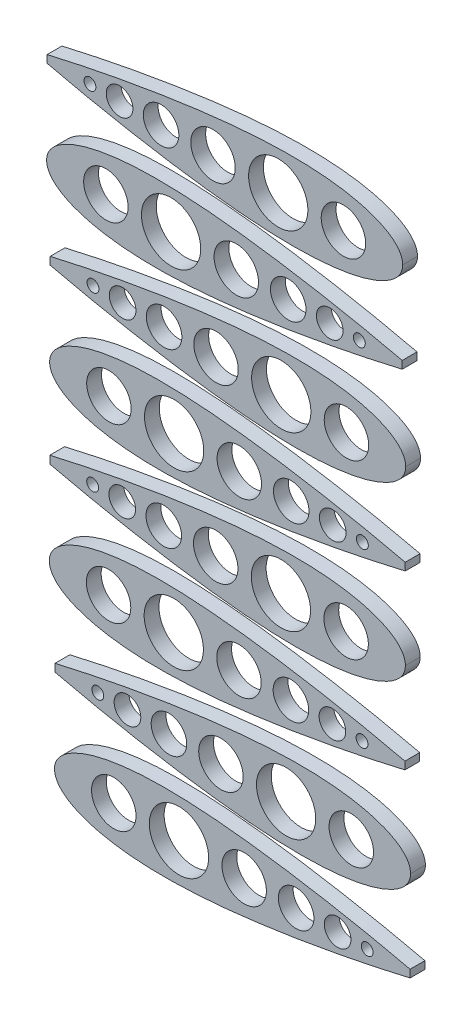
SolidWorks part; units mm, degrees
ref_plane "Front Plane" through (0, 0, 0) normal (0, 0, 1) x (1, 0, 0)
ref_plane "Top Plane" through (0, 0, 0) normal (0, 1, 0) x (1, 0, 0)
ref_plane "Right Plane" through (0, 0, 0) normal (1, 0, 0) x (0, 0, -1)
sketch "Sketch3" plane through (0, 0, 0) normal (0, 0, 1) x (1, 0, 0)
  line L0 (-2.0822, 0.1609) -> (48.226, 0.2196) construction
  line L2 (45.9178, 0.7504) -> (45.9194, -0.2774)
  line L5 (-2.0196, 12.5385) -> (-2.0213, 11.5107)
  line L6 (-2.7831, 24.1357) -> (47.5252, 24.1944) construction
  line L7 (45.2169, 24.7252) -> (45.2185, 23.6974)
  line L9 (-2.7205, 36.5133) -> (-2.7221, 35.4855)
  line L10 (-2.7381, 47.4071) -> (47.5702, 47.4659) construction
  line L11 (45.2619, 47.9966) -> (45.2635, 46.9688)
  line L13 (-2.6755, 59.7848) -> (-2.6771, 58.757)
  line L14 (-3.1458, 70.7938) -> (47.1624, 70.8526) construction
  line L15 (44.8542, 71.3834) -> (44.8558, 70.3556)
  line L17 (-3.0833, 83.1715) -> (-3.0849, 82.1437)
  circle A0 centre (5.9178, 0.1702) radius 3
  circle A1 centre (23.5178, 0.1908) radius 3
  circle A2 centre (30.5311, 0.1989) radius 2.4
  circle A3 centre (36.1311, 0.2055) radius 1.8
  circle A4 centre (14.7178, 0.1805) radius 4
  circle A5 centre (40.1311, 0.2102) radius 0.8
  circle A12 centre (3.7671, 11.9983) radius 0.8
  circle A13 centre (29.1804, 11.9686) radius 4
  circle A14 centre (7.7671, 11.9936) radius 1.8
  circle A15 centre (13.3671, 11.9871) radius 2.4
  circle A16 centre (20.3804, 11.9789) radius 3
  circle A17 centre (37.9804, 11.9584) radius 3
  circle A18 centre (5.2169, 24.145) radius 3
  circle A19 centre (22.8169, 24.1656) radius 3
  circle A20 centre (29.8302, 24.1737) radius 2.4
  circle A21 centre (35.4302, 24.1803) radius 1.8
  circle A22 centre (14.0169, 24.1553) radius 4
  circle A23 centre (39.4302, 24.185) radius 0.8
  circle A24 centre (3.0662, 35.9731) radius 0.8
  circle A25 centre (28.4795, 35.9434) radius 4
  circle A26 centre (7.0662, 35.9684) radius 1.8
  circle A27 centre (12.6662, 35.9619) radius 2.4
  circle A28 centre (19.6795, 35.9537) radius 3
  circle A29 centre (37.2795, 35.9332) radius 3
  circle A30 centre (5.2619, 47.4164) radius 3
  circle A31 centre (22.8619, 47.437) radius 3
  circle A32 centre (29.8752, 47.4452) radius 2.4
  circle A33 centre (35.4752, 47.4517) radius 1.8
  circle A34 centre (14.0619, 47.4267) radius 4
  circle A35 centre (39.4752, 47.4564) radius 0.8
  circle A36 centre (3.1112, 59.2446) radius 0.8
  circle A37 centre (28.5245, 59.2149) radius 4
  circle A38 centre (7.1112, 59.2399) radius 1.8
  circle A39 centre (12.7112, 59.2333) radius 2.4
  circle A40 centre (19.7245, 59.2252) radius 3
  circle A41 centre (37.3245, 59.2046) radius 3
  circle A42 centre (4.8542, 70.8032) radius 3
  circle A43 centre (22.4542, 70.8237) radius 3
  circle A44 centre (29.4675, 70.8319) radius 2.4
  circle A45 centre (35.0675, 70.8385) radius 1.8
  circle A46 centre (13.6542, 70.8135) radius 4
  circle A47 centre (39.0675, 70.8431) radius 0.8
  circle A48 centre (2.7035, 82.6313) radius 0.8
  circle A49 centre (28.1167, 82.6016) radius 4
  circle A50 centre (6.7035, 82.6266) radius 1.8
  circle A51 centre (12.3035, 82.6201) radius 2.4
  circle A52 centre (19.3167, 82.6119) radius 3
  circle A53 centre (36.9167, 82.5913) radius 3
  spline S0 degree 4 poles (-2.0822, 0.1609) (-2.0822, 0.2501) (-2.0745, 0.4065) (-2.0434, 0.6321) (-1.9635, 0.9266) (-1.851, 1.2077) (-1.691, 1.503) (-1.4676, 1.8208) (-1.1589, 2.1675) (-0.73, 2.5509) (-0.1308, 2.9765) (0.6883, 3.4341) (1.8328, 3.9286) (3.2718, 4.3898) (5.3571, 4.8716) (8.0704, 5.2479) (11.2639, 5.4401) (14.9251, 5.4194) (18.1506, 5.2444) (20.9119, 5.0088) (23.6627, 4.7182) (25.9589, 4.4324) (28.2343, 4.1154) (30.9873, 3.6918) (33.2354, 3.3202) (35.5537, 2.9055) (38.2028, 2.4079) (40.5964, 1.9241) (42.6302, 1.4985) (45.3856, 0.8778) (46.7254, 0.5626) (48.6266, 0.1007) (49.5206, -0.1314) (50.2383, -0.3142) (50.4788, -0.3788) (50.6372, -0.4202) (50.7214, -0.4421) knots 0 0 0 0 0 0.006442 0.011325 0.016406 0.022022 0.028285 0.035552 0.044435 0.055515 0.069795 0.088588 0.11215 0.14552 0.17889 0.243189 0.30993 0.376671 0.443412 0.476782 0.510153 0.576893 0.610264 0.643634 0.710375 0.743746 0.777116 0.843857 0.877227 0.910598 0.955299 0.977649 0.988825 0.994412 1 1 1 1 1 construction
  spline S1 degree 4 poles (-2.0822, 0.1609) (-2.0822, 0.2501) (-2.0745, 0.4065) (-2.0434, 0.6321) (-1.9635, 0.9266) (-1.851, 1.2077) (-1.691, 1.503) (-1.4676, 1.8208) (-1.1589, 2.1675) (-0.73, 2.5509) (-0.1308, 2.9765) (0.6883, 3.4341) (1.8328, 3.9286) (3.2718, 4.3898) (5.3571, 4.8716) (8.0704, 5.2479) (11.2639, 5.4401) (14.9251, 5.4194) (18.1506, 5.2444) (20.9119, 5.0088) (23.6627, 4.7182) (25.9589, 4.4324) (28.2343, 4.1154) (30.9873, 3.6918) (33.2354, 3.3202) (35.5537, 2.9055) (38.2028, 2.4079) (40.5964, 1.9241) (42.6302, 1.4985) (44.6943, 1.0335) (45.5086, 0.8461) (45.9178, 0.7504) knots 0 0 0 0 0 0.006442 0.011325 0.016406 0.022022 0.028285 0.035552 0.044435 0.055515 0.069795 0.088588 0.11215 0.14552 0.17889 0.243189 0.30993 0.376671 0.443412 0.476782 0.510153 0.576893 0.610264 0.643634 0.710375 0.743746 0.777116 0.843857 0.877227 0.910598 0.910598 0.910598 0.910598 0.910598
  spline S2 degree 4 poles (-2.0822, 0.1609) (-2.082, 0.0716) (-2.0737, -0.0848) (-2.0419, -0.3102) (-1.961, -0.6045) (-1.8477, -0.8853) (-1.6867, -1.18) (-1.4624, -1.4972) (-1.1526, -1.8429) (-0.7225, -2.2249) (-0.1219, -2.6487) (0.6986, -3.1036) (1.8446, -3.5946) (3.2851, -4.0512) (5.3719, -4.5264) (8.0864, -4.8942) (11.2805, -5.0764) (14.9416, -5.044) (18.1665, -4.8589) (20.9271, -4.6147) (23.6769, -4.3153) (25.9722, -4.0223) (28.2466, -3.6982) (30.9983, -3.2659) (33.2452, -2.8873) (35.5621, -2.4652) (38.2097, -1.9593) (40.6018, -1.468) (42.6342, -1.0359) (44.6969, -0.5644) (45.5105, -0.3744) (45.9194, -0.2774) knots 0 0 0 0 0 0.006442 0.011325 0.016406 0.022022 0.028285 0.035552 0.044435 0.055515 0.069795 0.088588 0.11215 0.14552 0.17889 0.243189 0.30993 0.376671 0.443412 0.476782 0.510153 0.576893 0.610264 0.643634 0.710375 0.743746 0.777116 0.843857 0.877227 0.910598 0.910598 0.910598 0.910598 0.910598
  spline S3 degree 4 poles (-2.7831, 24.1357) (-2.7831, 24.2249) (-2.7754, 24.3813) (-2.7442, 24.6069) (-2.6643, 24.9014) (-2.5519, 25.1825) (-2.3918, 25.4778) (-2.1685, 25.7956) (-1.8598, 26.1423) (-1.4309, 26.5257) (-0.8317, 26.9513) (-0.0125, 27.4089) (1.1319, 27.9034) (2.5709, 28.3646) (4.6562, 28.8464) (7.3695, 29.2228) (10.5631, 29.4149) (14.2242, 29.3942) (17.4498, 29.2192) (20.211, 28.9837) (22.9618, 28.693) (25.258, 28.4072) (27.5334, 28.0902) (30.2864, 27.6666) (32.5346, 27.2951) (34.8528, 26.8803) (37.502, 26.3827) (39.8956, 25.8989) (41.9293, 25.4733) (44.6847, 24.8526) (46.0245, 24.5374) (47.9257, 24.0755) (48.8197, 23.8434) (49.5374, 23.6606) (49.778, 23.596) (49.9364, 23.5546) (50.0205, 23.5327) knots 0 0 0 0 0 0.006442 0.011325 0.016406 0.022022 0.028285 0.035552 0.044435 0.055515 0.069795 0.088588 0.11215 0.14552 0.17889 0.243189 0.30993 0.376671 0.443412 0.476782 0.510153 0.576893 0.610264 0.643634 0.710375 0.743746 0.777116 0.843857 0.877227 0.910598 0.955299 0.977649 0.988825 0.994412 1 1 1 1 1 construction
  spline S4 degree 4 poles (-2.7831, 24.1357) (-2.7831, 24.2249) (-2.7754, 24.3813) (-2.7442, 24.6069) (-2.6643, 24.9014) (-2.5519, 25.1825) (-2.3918, 25.4778) (-2.1685, 25.7956) (-1.8598, 26.1423) (-1.4309, 26.5257) (-0.8317, 26.9513) (-0.0125, 27.4089) (1.1319, 27.9034) (2.5709, 28.3646) (4.6562, 28.8464) (7.3695, 29.2228) (10.5631, 29.4149) (14.2242, 29.3942) (17.4498, 29.2192) (20.211, 28.9837) (22.9618, 28.693) (25.258, 28.4072) (27.5334, 28.0902) (30.2864, 27.6666) (32.5346, 27.2951) (34.8528, 26.8803) (37.502, 26.3827) (39.8956, 25.8989) (41.9293, 25.4733) (43.9935, 25.0083) (44.8077, 24.8209) (45.2169, 24.7252) knots 0 0 0 0 0 0.006442 0.011325 0.016406 0.022022 0.028285 0.035552 0.044435 0.055515 0.069795 0.088588 0.11215 0.14552 0.17889 0.243189 0.30993 0.376671 0.443412 0.476782 0.510153 0.576893 0.610264 0.643634 0.710375 0.743746 0.777116 0.843857 0.877227 0.910598 0.910598 0.910598 0.910598 0.910598
  spline S5 degree 4 poles (45.9804, 11.949) (45.9801, 11.8598) (45.9719, 11.7034) (45.94, 11.4779) (45.8592, 11.1836) (45.7458, 10.9029) (45.5849, 10.6082) (45.3606, 10.291) (45.0507, 9.9453) (44.6206, 9.5632) (44.0201, 9.1395) (43.1995, 8.6846) (42.0535, 8.1936) (40.6131, 7.737) (38.5262, 7.2617) (35.8118, 6.8939) (32.6177, 6.7118) (28.9566, 6.7441) (25.7316, 6.9293) (22.9711, 7.1735) (20.2212, 7.4728) (17.9259, 7.7659) (15.6515, 8.09) (12.8999, 8.5223) (10.653, 8.9009) (8.336, 9.3229) (5.6884, 9.8289) (3.2964, 10.3202) (1.264, 10.7523) (-0.7987, 11.2238) (-1.6123, 11.4137) (-2.0213, 11.5107) knots 0 0 0 0 0 0.006442 0.011325 0.016406 0.022022 0.028285 0.035552 0.044435 0.055515 0.069795 0.088588 0.11215 0.14552 0.17889 0.243189 0.30993 0.376671 0.443412 0.476782 0.510153 0.576893 0.610264 0.643634 0.710375 0.743746 0.777116 0.843857 0.877227 0.910598 0.910598 0.910598 0.910598 0.910598
  spline S6 degree 4 poles (45.9804, 11.949) (45.9804, 12.0382) (45.9727, 12.1947) (45.9415, 12.4202) (45.8616, 12.7148) (45.7491, 12.9959) (45.5891, 13.2911) (45.3658, 13.609) (45.0571, 13.9557) (44.6281, 14.3391) (44.029, 14.7647) (43.2098, 15.2222) (42.0654, 15.7168) (40.6264, 16.178) (38.541, 16.6598) (35.8278, 17.0361) (32.6342, 17.2283) (28.973, 17.2075) (25.7475, 17.0325) (22.9862, 16.797) (20.2355, 16.5063) (17.9392, 16.2205) (15.6639, 15.9036) (12.9108, 15.48) (10.6627, 15.1084) (8.3445, 14.6937) (5.6953, 14.1961) (3.3017, 13.7123) (1.268, 13.2866) (-0.7962, 12.8216) (-1.6104, 12.6342) (-2.0196, 12.5385) knots 0 0 0 0 0 0.006442 0.011325 0.016406 0.022022 0.028285 0.035552 0.044435 0.055515 0.069795 0.088588 0.11215 0.14552 0.17889 0.243189 0.30993 0.376671 0.443412 0.476782 0.510153 0.576893 0.610264 0.643634 0.710375 0.743746 0.777116 0.843857 0.877227 0.910598 0.910598 0.910598 0.910598 0.910598
  spline S7 degree 4 poles (-2.7831, 24.1357) (-2.7828, 24.0464) (-2.7746, 23.89) (-2.7428, 23.6646) (-2.6619, 23.3703) (-2.5486, 23.0895) (-2.3876, 22.7948) (-2.1633, 22.4776) (-1.8535, 22.1319) (-1.4233, 21.7499) (-0.8228, 21.3261) (-0.0022, 20.8712) (1.1438, 20.3802) (2.5842, 19.9236) (4.671, 19.4484) (7.3855, 19.0806) (10.5796, 18.8984) (14.2407, 18.9308) (17.4657, 19.1159) (20.2262, 19.3601) (22.976, 19.6595) (25.2714, 19.9525) (27.5457, 20.2766) (30.2974, 20.7089) (32.5443, 21.0875) (34.8613, 21.5096) (37.5088, 22.0155) (39.9009, 22.5068) (41.9333, 22.9389) (43.996, 23.4104) (44.8096, 23.6004) (45.2185, 23.6974) knots 0 0 0 0 0 0.006442 0.011325 0.016406 0.022022 0.028285 0.035552 0.044435 0.055515 0.069795 0.088588 0.11215 0.14552 0.17889 0.243189 0.30993 0.376671 0.443412 0.476782 0.510153 0.576893 0.610264 0.643634 0.710375 0.743746 0.777116 0.843857 0.877227 0.910598 0.910598 0.910598 0.910598 0.910598
  spline S8 degree 4 poles (45.2795, 35.9238) (45.2792, 35.8346) (45.271, 35.6782) (45.2392, 35.4527) (45.1583, 35.1584) (45.045, 34.8777) (44.884, 34.583) (44.6597, 34.2658) (44.3499, 33.9201) (43.9197, 33.538) (43.3192, 33.1143) (42.4986, 32.6594) (41.3526, 32.1684) (39.9122, 31.7118) (37.8254, 31.2365) (35.1109, 30.8687) (31.9168, 30.6866) (28.2557, 30.7189) (25.0307, 30.9041) (22.2702, 31.1483) (19.5204, 31.4476) (17.225, 31.7407) (14.9507, 32.0648) (12.199, 32.4971) (9.9521, 32.8757) (7.6351, 33.2977) (4.9876, 33.8037) (2.5955, 34.295) (0.5631, 34.7271) (-1.4996, 35.1986) (-2.3132, 35.3885) (-2.7221, 35.4855) knots 0 0 0 0 0 0.006442 0.011325 0.016406 0.022022 0.028285 0.035552 0.044435 0.055515 0.069795 0.088588 0.11215 0.14552 0.17889 0.243189 0.30993 0.376671 0.443412 0.476782 0.510153 0.576893 0.610264 0.643634 0.710375 0.743746 0.777116 0.843857 0.877227 0.910598 0.910598 0.910598 0.910598 0.910598
  spline S9 degree 4 poles (45.2795, 35.9238) (45.2795, 36.013) (45.2718, 36.1695) (45.2407, 36.395) (45.1607, 36.6896) (45.0483, 36.9707) (44.8882, 37.2659) (44.6649, 37.5838) (44.3562, 37.9305) (43.9273, 38.3139) (43.3281, 38.7395) (42.5089, 39.197) (41.3645, 39.6916) (39.9255, 40.1528) (37.8402, 40.6346) (35.1269, 41.0109) (31.9334, 41.2031) (28.2722, 41.1823) (25.0466, 41.0073) (22.2854, 40.7718) (19.5346, 40.4811) (17.2384, 40.1953) (14.963, 39.8784) (12.21, 39.4548) (9.9619, 39.0832) (7.6436, 38.6685) (4.9944, 38.1709) (2.6008, 37.6871) (0.5671, 37.2614) (-1.4971, 36.7964) (-2.3113, 36.609) (-2.7205, 36.5133) knots 0 0 0 0 0 0.006442 0.011325 0.016406 0.022022 0.028285 0.035552 0.044435 0.055515 0.069795 0.088588 0.11215 0.14552 0.17889 0.243189 0.30993 0.376671 0.443412 0.476782 0.510153 0.576893 0.610264 0.643634 0.710375 0.743746 0.777116 0.843857 0.877227 0.910598 0.910598 0.910598 0.910598 0.910598
  spline S10 degree 4 poles (-2.7381, 47.4071) (-2.7381, 47.4963) (-2.7304, 47.6528) (-2.6993, 47.8783) (-2.6193, 48.1729) (-2.5069, 48.454) (-2.3468, 48.7492) (-2.1235, 49.0671) (-1.8148, 49.4138) (-1.3859, 49.7972) (-0.7867, 50.2228) (0.0325, 50.6803) (1.1769, 51.1749) (2.6159, 51.636) (4.7012, 52.1179) (7.4145, 52.4942) (10.6081, 52.6864) (14.2692, 52.6656) (17.4948, 52.4906) (20.256, 52.2551) (23.0068, 51.9644) (25.303, 51.6786) (27.5784, 51.3617) (30.3314, 50.938) (32.5796, 50.5665) (34.8978, 50.1518) (37.547, 49.6542) (39.9406, 49.1704) (41.9743, 48.7447) (44.7297, 48.124) (46.0695, 47.8089) (47.9707, 47.3469) (48.8647, 47.1149) (49.5824, 46.932) (49.823, 46.8674) (49.9813, 46.8261) (50.0655, 46.8042) knots 0 0 0 0 0 0.006442 0.011325 0.016406 0.022022 0.028285 0.035552 0.044435 0.055515 0.069795 0.088588 0.11215 0.14552 0.17889 0.243189 0.30993 0.376671 0.443412 0.476782 0.510153 0.576893 0.610264 0.643634 0.710375 0.743746 0.777116 0.843857 0.877227 0.910598 0.955299 0.977649 0.988825 0.994412 1 1 1 1 1 construction
  spline S11 degree 4 poles (-2.7381, 47.4071) (-2.7381, 47.4963) (-2.7304, 47.6528) (-2.6993, 47.8783) (-2.6193, 48.1729) (-2.5069, 48.454) (-2.3468, 48.7492) (-2.1235, 49.0671) (-1.8148, 49.4138) (-1.3859, 49.7972) (-0.7867, 50.2228) (0.0325, 50.6803) (1.1769, 51.1749) (2.6159, 51.636) (4.7012, 52.1179) (7.4145, 52.4942) (10.6081, 52.6864) (14.2692, 52.6656) (17.4948, 52.4906) (20.256, 52.2551) (23.0068, 51.9644) (25.303, 51.6786) (27.5784, 51.3617) (30.3314, 50.938) (32.5796, 50.5665) (34.8978, 50.1518) (37.547, 49.6542) (39.9406, 49.1704) (41.9743, 48.7447) (44.0385, 48.2797) (44.8527, 48.0923) (45.2619, 47.9966) knots 0 0 0 0 0 0.006442 0.011325 0.016406 0.022022 0.028285 0.035552 0.044435 0.055515 0.069795 0.088588 0.11215 0.14552 0.17889 0.243189 0.30993 0.376671 0.443412 0.476782 0.510153 0.576893 0.610264 0.643634 0.710375 0.743746 0.777116 0.843857 0.877227 0.910598 0.910598 0.910598 0.910598 0.910598
  spline S12 degree 4 poles (-2.7381, 47.4071) (-2.7378, 47.3179) (-2.7296, 47.1615) (-2.6978, 46.936) (-2.6169, 46.6417) (-2.5036, 46.361) (-2.3426, 46.0663) (-2.1183, 45.7491) (-1.8085, 45.4034) (-1.3783, 45.0213) (-0.7778, 44.5976) (0.0428, 44.1427) (1.1888, 43.6517) (2.6292, 43.1951) (4.716, 42.7198) (7.4305, 42.352) (10.6246, 42.1699) (14.2857, 42.2022) (17.5107, 42.3873) (20.2712, 42.6316) (23.021, 42.9309) (25.3164, 43.2239) (27.5907, 43.5481) (30.3424, 43.9803) (32.5893, 44.359) (34.9063, 44.781) (37.5538, 45.287) (39.9459, 45.7783) (41.9783, 46.2104) (44.041, 46.6818) (44.8546, 46.8718) (45.2635, 46.9688) knots 0 0 0 0 0 0.006442 0.011325 0.016406 0.022022 0.028285 0.035552 0.044435 0.055515 0.069795 0.088588 0.11215 0.14552 0.17889 0.243189 0.30993 0.376671 0.443412 0.476782 0.510153 0.576893 0.610264 0.643634 0.710375 0.743746 0.777116 0.843857 0.877227 0.910598 0.910598 0.910598 0.910598 0.910598
  spline S13 degree 4 poles (45.3245, 59.1953) (45.3242, 59.106) (45.316, 58.9496) (45.2842, 58.7242) (45.2033, 58.4299) (45.09, 58.1491) (44.929, 57.8544) (44.7047, 57.5372) (44.3949, 57.1915) (43.9647, 56.8095) (43.3642, 56.3857) (42.5436, 55.9308) (41.3976, 55.4398) (39.9572, 54.9832) (37.8704, 54.508) (35.1559, 54.1402) (31.9618, 53.958) (28.3007, 53.9904) (25.0757, 54.1755) (22.3152, 54.4197) (19.5654, 54.7191) (17.27, 55.0121) (14.9957, 55.3362) (12.244, 55.7685) (9.9971, 56.1471) (7.6801, 56.5692) (5.0326, 57.0751) (2.6405, 57.5664) (0.6081, 57.9985) (-1.4546, 58.47) (-2.2682, 58.66) (-2.6771, 58.757) knots 0 0 0 0 0 0.006442 0.011325 0.016406 0.022022 0.028285 0.035552 0.044435 0.055515 0.069795 0.088588 0.11215 0.14552 0.17889 0.243189 0.30993 0.376671 0.443412 0.476782 0.510153 0.576893 0.610264 0.643634 0.710375 0.743746 0.777116 0.843857 0.877227 0.910598 0.910598 0.910598 0.910598 0.910598
  spline S14 degree 4 poles (45.3245, 59.1953) (45.3245, 59.2845) (45.3168, 59.4409) (45.2857, 59.6665) (45.2057, 59.961) (45.0933, 60.2421) (44.9332, 60.5374) (44.7099, 60.8552) (44.4012, 61.2019) (43.9723, 61.5853) (43.3731, 62.0109) (42.5539, 62.4685) (41.4095, 62.963) (39.9705, 63.4242) (37.8852, 63.906) (35.1719, 64.2823) (31.9783, 64.4745) (28.3172, 64.4538) (25.0916, 64.2788) (22.3304, 64.0433) (19.5796, 63.7526) (17.2834, 63.4668) (15.008, 63.1498) (12.255, 62.7262) (10.0069, 62.3546) (7.6886, 61.9399) (5.0394, 61.4423) (2.6458, 60.9585) (0.6121, 60.5329) (-1.4521, 60.0679) (-2.2663, 59.8805) (-2.6755, 59.7848) knots 0 0 0 0 0 0.006442 0.011325 0.016406 0.022022 0.028285 0.035552 0.044435 0.055515 0.069795 0.088588 0.11215 0.14552 0.17889 0.243189 0.30993 0.376671 0.443412 0.476782 0.510153 0.576893 0.610264 0.643634 0.710375 0.743746 0.777116 0.843857 0.877227 0.910598 0.910598 0.910598 0.910598 0.910598
  spline S15 degree 4 poles (-3.1458, 70.7938) (-3.1458, 70.8831) (-3.1381, 71.0395) (-3.107, 71.2651) (-3.0271, 71.5596) (-2.9146, 71.8407) (-2.7546, 72.1359) (-2.5312, 72.4538) (-2.2225, 72.8005) (-1.7936, 73.1839) (-1.1944, 73.6095) (-0.3753, 74.067) (0.7692, 74.5616) (2.2082, 75.0228) (4.2935, 75.5046) (7.0068, 75.8809) (10.2003, 76.0731) (13.8615, 76.0524) (17.087, 75.8774) (19.8483, 75.6418) (22.5991, 75.3512) (24.8953, 75.0654) (27.1707, 74.7484) (29.9237, 74.3248) (32.1718, 73.9532) (34.4901, 73.5385) (37.1392, 73.0409) (39.5328, 72.5571) (41.5666, 72.1314) (44.322, 71.5107) (45.6618, 71.1956) (47.563, 70.7336) (48.457, 70.5016) (49.1746, 70.3188) (49.4152, 70.2542) (49.5736, 70.2128) (49.6577, 70.1909) knots 0 0 0 0 0 0.006442 0.011325 0.016406 0.022022 0.028285 0.035552 0.044435 0.055515 0.069795 0.088588 0.11215 0.14552 0.17889 0.243189 0.30993 0.376671 0.443412 0.476782 0.510153 0.576893 0.610264 0.643634 0.710375 0.743746 0.777116 0.843857 0.877227 0.910598 0.955299 0.977649 0.988825 0.994412 1 1 1 1 1 construction
  spline S16 degree 4 poles (-3.1458, 70.7938) (-3.1458, 70.8831) (-3.1381, 71.0395) (-3.107, 71.2651) (-3.0271, 71.5596) (-2.9146, 71.8407) (-2.7546, 72.1359) (-2.5312, 72.4538) (-2.2225, 72.8005) (-1.7936, 73.1839) (-1.1944, 73.6095) (-0.3753, 74.067) (0.7692, 74.5616) (2.2082, 75.0228) (4.2935, 75.5046) (7.0068, 75.8809) (10.2003, 76.0731) (13.8615, 76.0524) (17.087, 75.8774) (19.8483, 75.6418) (22.5991, 75.3512) (24.8953, 75.0654) (27.1707, 74.7484) (29.9237, 74.3248) (32.1718, 73.9532) (34.4901, 73.5385) (37.1392, 73.0409) (39.5328, 72.5571) (41.5666, 72.1314) (43.6307, 71.6665) (44.445, 71.4791) (44.8542, 71.3834) knots 0 0 0 0 0 0.006442 0.011325 0.016406 0.022022 0.028285 0.035552 0.044435 0.055515 0.069795 0.088588 0.11215 0.14552 0.17889 0.243189 0.30993 0.376671 0.443412 0.476782 0.510153 0.576893 0.610264 0.643634 0.710375 0.743746 0.777116 0.843857 0.877227 0.910598 0.910598 0.910598 0.910598 0.910598
  spline S17 degree 4 poles (-3.1458, 70.7938) (-3.1456, 70.7046) (-3.1374, 70.5482) (-3.1055, 70.3228) (-3.0247, 70.0285) (-2.9113, 69.7477) (-2.7503, 69.453) (-2.526, 69.1358) (-2.2162, 68.7901) (-1.7861, 68.408) (-1.1856, 67.9843) (-0.365, 67.5294) (0.781, 67.0384) (2.2215, 66.5818) (4.3083, 66.1066) (7.0227, 65.7388) (10.2169, 65.5566) (13.878, 65.5889) (17.1029, 65.7741) (19.8635, 66.0183) (22.6133, 66.3176) (24.9086, 66.6107) (27.183, 66.9348) (29.9347, 67.3671) (32.1816, 67.7457) (34.4985, 68.1678) (37.1461, 68.6737) (39.5382, 69.165) (41.5706, 69.5971) (43.6332, 70.0686) (44.4469, 70.2586) (44.8558, 70.3556) knots 0 0 0 0 0 0.006442 0.011325 0.016406 0.022022 0.028285 0.035552 0.044435 0.055515 0.069795 0.088588 0.11215 0.14552 0.17889 0.243189 0.30993 0.376671 0.443412 0.476782 0.510153 0.576893 0.610264 0.643634 0.710375 0.743746 0.777116 0.843857 0.877227 0.910598 0.910598 0.910598 0.910598 0.910598
  spline S18 degree 4 poles (44.9167, 82.582) (44.9165, 82.4928) (44.9083, 82.3364) (44.8764, 82.1109) (44.7956, 81.8166) (44.6822, 81.5359) (44.5213, 81.2412) (44.2969, 80.924) (43.9871, 80.5783) (43.557, 80.1962) (42.9565, 79.7725) (42.1359, 79.3176) (40.9899, 78.8266) (39.5494, 78.37) (37.4626, 77.8947) (34.7482, 77.5269) (31.554, 77.3448) (27.893, 77.3771) (24.668, 77.5622) (21.9075, 77.8065) (19.1576, 78.1058) (16.8623, 78.3988) (14.5879, 78.723) (11.8363, 79.1552) (9.5893, 79.5339) (7.2724, 79.9559) (4.6248, 80.4618) (2.2328, 80.9532) (0.2004, 81.3853) (-1.8623, 81.8567) (-2.676, 82.0467) (-3.0849, 82.1437) knots 0 0 0 0 0 0.006442 0.011325 0.016406 0.022022 0.028285 0.035552 0.044435 0.055515 0.069795 0.088588 0.11215 0.14552 0.17889 0.243189 0.30993 0.376671 0.443412 0.476782 0.510153 0.576893 0.610264 0.643634 0.710375 0.743746 0.777116 0.843857 0.877227 0.910598 0.910598 0.910598 0.910598 0.910598
  spline S19 degree 4 poles (44.9167, 82.582) (44.9168, 82.6712) (44.9091, 82.8277) (44.8779, 83.0532) (44.798, 83.3478) (44.6855, 83.6289) (44.5255, 83.9241) (44.3022, 84.242) (43.9934, 84.5887) (43.5645, 84.9721) (42.9653, 85.3977) (42.1462, 85.8552) (41.0017, 86.3498) (39.5627, 86.8109) (37.4774, 87.2928) (34.7642, 87.6691) (31.5706, 87.8613) (27.9094, 87.8405) (24.6839, 87.6655) (21.9226, 87.43) (19.1719, 87.1393) (16.8756, 86.8535) (14.6002, 86.5366) (11.8472, 86.1129) (9.5991, 85.7414) (7.2809, 85.3267) (4.6317, 84.8291) (2.2381, 84.3453) (0.2043, 83.9196) (-1.8598, 83.4546) (-2.674, 83.2672) (-3.0833, 83.1715) knots 0 0 0 0 0 0.006442 0.011325 0.016406 0.022022 0.028285 0.035552 0.044435 0.055515 0.069795 0.088588 0.11215 0.14552 0.17889 0.243189 0.30993 0.376671 0.443412 0.476782 0.510153 0.576893 0.610264 0.643634 0.710375 0.743746 0.777116 0.843857 0.877227 0.910598 0.910598 0.910598 0.910598 0.910598
  point P5 (5.9178, 0.1702)
  point P6 (23.5178, 0.1908)
  point P12 (30.5311, 0.1989)
  point P13 (36.1311, 0.2055)
  point P14 (45.9186, 0.2365)
  point P15 (14.7178, 0.1805)
  point P22 (40.1311, 0.2102)
  point P31 (5.2169, 24.145)
  point P32 (22.8169, 24.1656)
  point P38 (29.8302, 24.1737)
  point P39 (35.4302, 24.1803)
  point P40 (45.2177, 24.2113)
  point P41 (14.0169, 24.1553)
  point P63 (3.7671, 11.9983)
  point P64 (29.1804, 11.9686)
  point P65 (-2.0205, 12.0246)
  point P66 (7.7671, 11.9936)
  point P67 (13.3671, 11.9871)
  point P68 (20.3804, 11.9789)
  point P69 (37.9804, 11.9584)
  point P70 (39.4302, 24.185)
  point P89 (3.0662, 35.9731)
  point P90 (28.4795, 35.9434)
  point P91 (-2.7213, 35.9994)
  point P92 (7.0662, 35.9684)
  point P93 (12.6662, 35.9619)
  point P94 (19.6795, 35.9537)
  point P95 (37.2795, 35.9332)
  point P101 (5.2619, 47.4164)
  point P102 (22.8619, 47.437)
  point P108 (29.8752, 47.4452)
  point P109 (35.4752, 47.4517)
  point P110 (45.2627, 47.4827)
  point P111 (14.0619, 47.4267)
  point P118 (39.4752, 47.4564)
  point P137 (3.1112, 59.2446)
  point P138 (28.5245, 59.2149)
  point P139 (-2.6763, 59.2709)
  point P140 (7.1112, 59.2399)
  point P141 (12.7112, 59.2333)
  point P142 (19.7245, 59.2252)
  point P143 (37.3245, 59.2046)
  point P149 (4.8542, 70.8032)
  point P150 (22.4542, 70.8237)
  point P156 (29.4675, 70.8319)
  point P157 (35.0675, 70.8385)
  point P158 (44.855, 70.8695)
  point P159 (13.6542, 70.8135)
  point P166 (39.0675, 70.8431)
  point P185 (2.7035, 82.6313)
  point P186 (28.1167, 82.6016)
  point P187 (-3.0841, 82.6576)
  point P188 (6.7035, 82.6266)
  point P189 (12.3035, 82.6201)
  point P190 (19.3167, 82.6119)
  point P191 (36.9167, 82.5913)
  dimension "D2" = 8
  dimension "D6" = 4
  dimension "D7" = 17.6
  dimension "D1" = 17.6
  dimension "D3" = 8.8
  dimension "D4" = 22.4008
  dimension "D5" = 5.6
  dimension "D8" = 8
  dimension "D9" = 8.8
  dimension "D10" = 22.4008
  dimension "D11" = 5.6
  dimension "D12" = 4
  dimension "D13" = 17.6
  dimension "D14" = 8
  dimension "D15" = 8.8
  dimension "D16" = 22.4008
  dimension "D17" = 5.6
  dimension "D18" = 4
  dimension "D19" = 17.6
  dimension "D20" = 8
  dimension "D21" = 8.8
  dimension "D22" = 22.4008
  dimension "D23" = 5.6
  dimension "D24" = 4
extrude "Boss-Extrude1" add sketch "Sketch3" along normal mid plane 2
